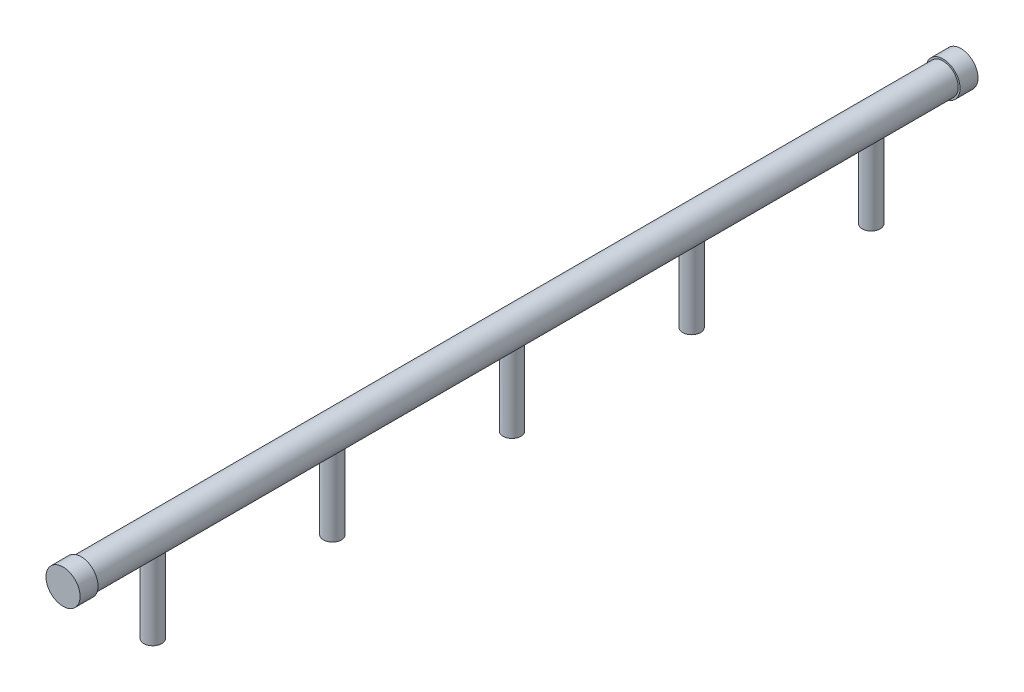
SolidWorks part; units mm, degrees
ref_plane "Front Plane" through (0, 0, 0) normal (0, 0, 1) x (1, 0, 0)
ref_plane "Top Plane" through (0, 0, 0) normal (0, 1, 0) x (1, 0, 0)
ref_plane "Right Plane" through (0, 0, 0) normal (1, 0, 0) x (0, 0, -1)
sketch "Sketch1" plane through (0, 0, 0) normal (0, 0, 1) x (1, 0, 0)
  circle A0 centre (0, 0) radius 17
  dimension "D1" = 34
extrude "Boss-Extrude1" add sketch "Sketch1" along normal blind 1000
sketch "Sketch2" plane through (0, 0, 1000) normal (0, 0, 1) x (1, 0, 0)
  circle A0 centre (0, 0) radius 19
  dimension "D1" = 38
extrude "Boss-Extrude2" add sketch "Sketch2" against normal blind 20
sketch "Sketch3" plane through (0, 0, 0) normal (0, 0, -1) x (-1, 0, 0)
  circle A0 centre (0, 0) radius 19
extrude "Boss-Extrude3" add sketch "Sketch3" against normal blind 20
sketch "Sketch4" plane through (0, 0, 0) normal (0, 1, 0) x (1, 0, 0)
  line L0 (-17, -20) -> (-17, -980) construction
  circle A0 centre (0, -500) radius 10
  circle A1 centre (0, -300) radius 10
  circle A2 centre (0, -100) radius 10
  circle A3 centre (0, -700) radius 10
  circle A4 centre (0, -900) radius 10
  dimension "D1" = 20
  dimension "D2" = 500
  dimension "D3" = 17
  dimension "D4" = 3
  dimension "D5" = 3
extrude "Boss-Extrude4" add sketch "Sketch4" against normal blind 100
